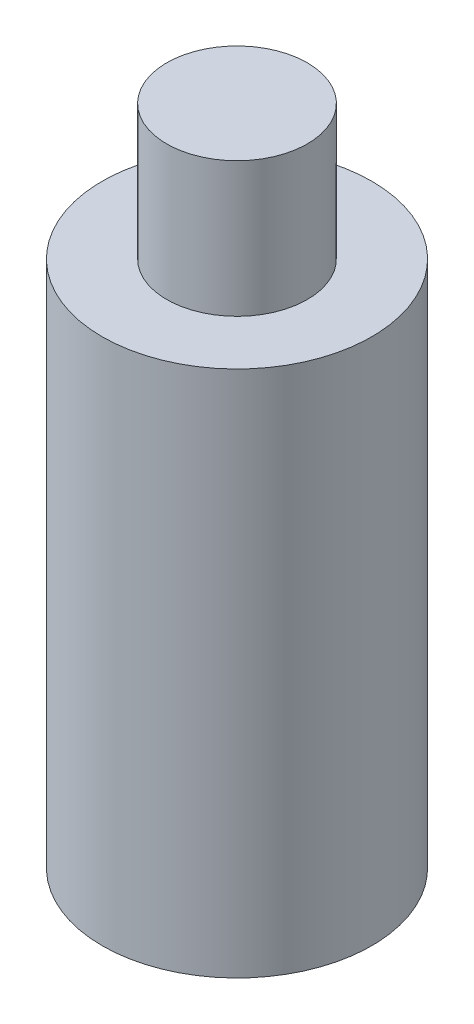
SolidWorks part; units mm, degrees
ref_plane "Front Plane" through (0, 0, 0) normal (0, 0, 1) x (1, 0, 0)
ref_plane "Top Plane" through (0, 0, 0) normal (0, 1, 0) x (1, 0, 0)
ref_plane "Right Plane" through (0, 0, 0) normal (1, 0, 0) x (0, 0, -1)
sketch "Sketch1" plane through (0, 0, 0) normal (0, 1, 0) x (1, 0, 0)
  circle A0 centre (0, 0) radius 7.62
  dimension "D1" = 15.24
extrude "Boss-Extrude1" add sketch "Sketch1" along normal blind 29.8196
sketch "Sketch2" plane through (0, 29.8196, 0) normal (0, 1, 0) x (1, 0, 0)
  circle A0 centre (0, 0) radius 3.975
  dimension "D1" = 7.95
extrude "Boss-Extrude2" add sketch "Sketch2" along normal blind 7.62
sketch "Sketch3" plane through (0, 0, 0) normal (0, -1, 0) x (1, 0, 0)
  line L0 (-5.08, 0) -> (5.08, 0) construction
  circle A0 centre (-5.08, 0) radius 1.1938
  circle A1 centre (5.08, 0) radius 1.1938
  point P2 (0, 0)
  dimension "D1" = 2.3876
  dimension "D2" = 10.16
extrude "Cut-Extrude1" cut sketch "Sketch3" against normal blind 7.8232
